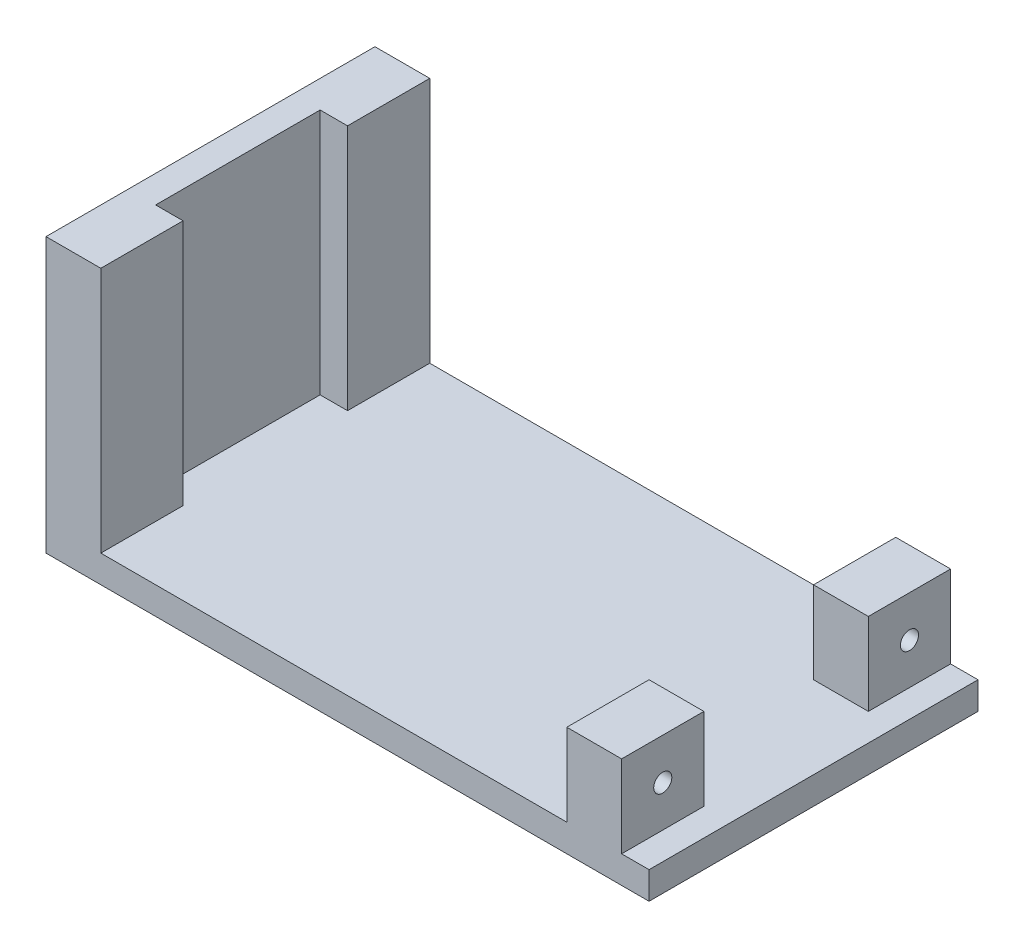
SolidWorks part; units mm, degrees
ref_plane "Alzado" through (0, 0, 0) normal (0, 0, 1) x (1, 0, 0)
ref_plane "Planta" through (0, 0, 0) normal (0, 1, 0) x (1, 0, 0)
ref_plane "Vista lateral" through (0, 0, 0) normal (1, 0, 0) x (0, 0, -1)
sketch "Croquis1" plane through (0, 0, 0) normal (0, 1, 0) x (1, 0, 0)
  line L1 (0, 0) -> (110, 0)
  line L2 (0, 0) -> (0, 60)
  line L3 (0, 60) -> (110, 60)
  line L4 (110, 0) -> (110, 60)
  dimension "D1" = 110
  dimension "D2" = 60
extrude "Saliente-Extruir1" add sketch "Croquis1" along normal blind 5
sketch "Croquis2" plane through (0, 5, 0) normal (0, 1, 0) x (1, 0, 0)
  line L0 (110, 60) -> (0, 60) construction
  line L1 (0, 0) -> (10, 0)
  line L2 (0, 0) -> (0, 60)
  line L3 (0, 60) -> (10, 60)
  line L4 (10, 0) -> (10, 15)
  line L5 (10, 45) -> (5, 45)
  line L6 (5, 45) -> (5, 15)
  line L7 (5, 15) -> (10, 15)
  line L8 (10, 45) -> (10, 60)
  dimension "D1" = 10
  dimension "D2" = 15
  dimension "D3" = 15
  dimension "D4" = 30
  dimension "D5" = 5
extrude "Saliente-Extruir2" add sketch "Croquis2" along normal blind 45
sketch "Croquis3" plane through (0, 0, 0) normal (-1, 0, 0) x (0, 0, 1)
  line L0 (-60, 50) -> (-52.5, 50) construction
  line L1 (-60, 50) -> (0, 50) construction
  line L2 (0, 0) -> (-7.5, 0) construction
  line L3 (-60, 0) -> (0, 0) construction
  line L4 (-7.5, 0) -> (-7.5, 5) construction
  line L5 (-7.5, 5) -> (-7.5, 10) construction
  line L6 (-52.5, 50) -> (-52.5, 40) construction
  point P14 (-52.5, 40)
  point P15 (-52.5, 40)
  point P16 (-7.5, 10)
  dimension "D1" = 7.5
  dimension "D2" = 7.5
  dimension "D3" = 5
  dimension "D4" = 5
  dimension "D5" = 10
sketch "Croquis4" plane through (0, 5, 0) normal (0, 1, 0) x (1, 0, 0)
  line L1 (110, 60) -> (95, 60)
  line L2 (110, 60) -> (110, 45)
  line L3 (110, 45) -> (95, 45)
  line L4 (95, 60) -> (95, 45)
  line L5 (110, 0) -> (95, 0)
  line L6 (110, 0) -> (110, 15)
  line L7 (110, 15) -> (95, 15)
  line L8 (95, 0) -> (95, 15)
  dimension "D1" = 15
  dimension "D2" = 15
  dimension "D3" = 15
  dimension "D4" = 15
extrude "Saliente-Extruir3" add sketch "Croquis4" along normal blind 15
sketch "Croquis5" plane through (110, 0, 0) normal (1, 0, 0) x (0, 0, -1)
  line L2 (15, 5) -> (0, 5)
  line L3 (15, 5) -> (15, 20)
  line L4 (15, 20) -> (0, 20)
  line L5 (0, 5) -> (0, 20)
  line L6 (45, 5) -> (60, 5)
  line L7 (45, 5) -> (45, 20)
  line L8 (45, 20) -> (60, 20)
  line L9 (60, 5) -> (60, 20)
extrude "Cortar-Extruir1" cut sketch "Croquis5" against normal blind 5
sketch "Croquis6" plane through (105, 0, 0) normal (1, 0, 0) x (0, 0, -1)
  line L0 (7.5, 5) -> (7.5, 12.5) construction
  line L1 (7.5, 12.5) -> (52.5, 12.5) construction
  line L2 (60, 5) -> (60, 20) construction
  point P7 (7.5, 12.5)
  point P8 (52.5, 12.5)
  dimension "D1" = 7.5
  dimension "D2" = 7.5
hole_wizard "Taladro roscado M41" positions "Croquis9" profile "Croquis10" tap size "M4" standard "DIN"
sketch "Croquis9" plane through (105, 0, 0) normal (1, 0, 0) x (0, 0, -1)
  point P0 (7.5, 12.5)
  point P3 (52.5, 12.5)
sketch "Croquis10" plane through (105, 12.5, -7.5) normal (0, 1, 0) x (0, 0, -1)
  line L0 (0, 0) -> (0, 15)
  line L1 (0, 15) -> (1.65, 14.0086)
  line L2 (1.65, 14.0086) -> (1.65, 0)
  line L5 (1.65, 0) -> (0, 0)
  line L10 (0, 15) -> (-1.65, 14.0086) construction
  line L11 (0, -6.35) -> (0, 107.95) construction
  dimension "Diámetro de perforador para roscar" = 3.3
  dimension "Profundidad de perforador para roscar" = 15
  dimension "Ángulo de perforador" = 118
cosmetic thread "Rosca de taladro1" parameters "D1"=8, "D2"=4
cosmetic thread "Rosca de taladro2" parameters "D1"=8, "D2"=4
sketch "Croquis11" plane through (0, 0, 0) normal (-1, 0, 0) x (0, 0, 1)
  line L0 (-60, 0) -> (0, 0) construction
  line L1 (-50, 34) -> (-45, 34)
  line L2 (-50, 34) -> (-50, 30)
  line L3 (-50, 30) -> (-45, 30)
  line L4 (-45, 34) -> (-45, 30)
  line L5 (-50, 34) -> (-45, 30) construction
  line L6 (-50, 30) -> (-45, 34) construction
  line L11 (-60, 50) -> (-60, 0) construction
  line L12 (-30, 0) -> (-30, 50) construction
  line L13 (-60, 50) -> (0, 50) construction
  line L14 (-10, 34) -> (-10, 30)
  line L15 (-10, 30) -> (-15, 34) construction
  line L16 (-10, 34) -> (-15, 30) construction
  line L17 (-10, 30) -> (-15, 30)
  line L18 (-15, 34) -> (-15, 30)
  line L19 (-10, 34) -> (-15, 34)
  point P0 (-47.5, 32)
  dimension "D1" = 30
  dimension "D2" = 10
  dimension "D3" = 5
  dimension "D4" = 4
extrude "Saliente-Extruir4" add sketch "Croquis11" along normal blind 3
sketch "Croquis12" plane through (-3, 0, 0) normal (-1, 0, 0) x (0, 0, 1)
  line L1 (-50, 34) -> (-10, 34)
  line L2 (-50, 34) -> (-50, 30)
  line L3 (-50, 30) -> (-10, 30)
  line L4 (-10, 34) -> (-10, 30)
extrude "Saliente-Extruir5" add sketch "Croquis12" along normal blind 2
